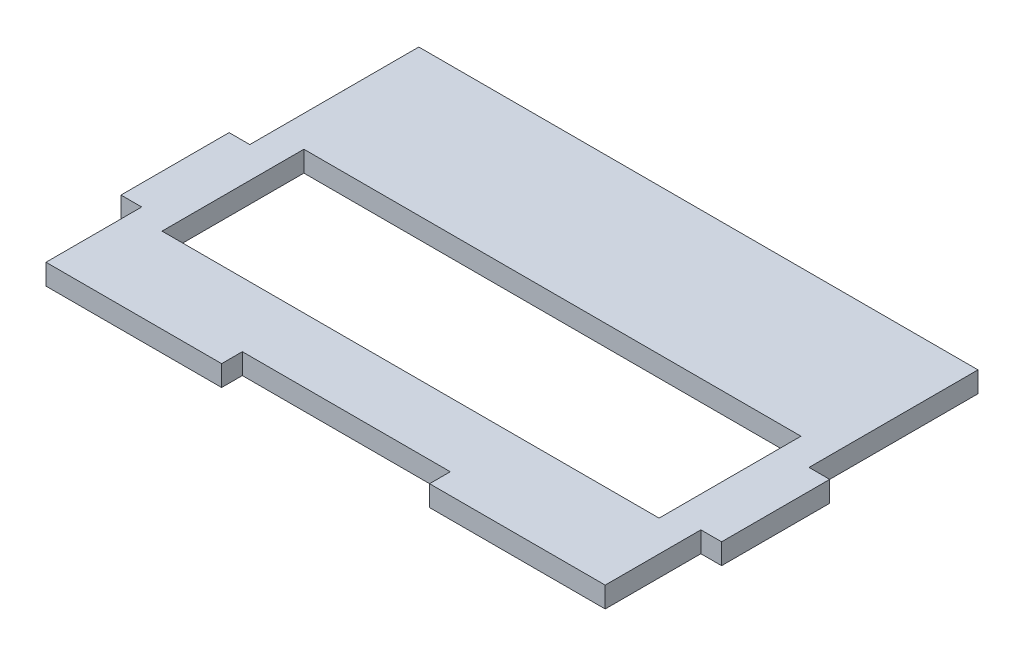
SolidWorks part; units mm, degrees
ref_plane "Front Plane" through (0, 0, 0) normal (0, 0, 1) x (1, 0, 0)
ref_plane "Top Plane" through (0, 0, 0) normal (0, 1, 0) x (1, 0, 0)
ref_plane "Right Plane" through (0, 0, 0) normal (1, 0, 0) x (0, 0, -1)
sketch "Sketch1" plane through (0, 0, 0) normal (0, 1, 0) x (1, 0, 0)
  line L1 (-72.5, -45) -> (72.5, -45)
  line L2 (-72.5, -45) -> (-72.5, 45)
  line L3 (-72.5, 45) -> (72.5, 45)
  line L4 (72.5, -45) -> (72.5, 45)
  line L5 (-72.5, -45) -> (72.5, 45) construction
  line L6 (-72.5, 45) -> (72.5, -45) construction
  point P0 (0, 0)
  dimension "D1" = 145
  dimension "D2" = 90
extrude "Boss-Extrude1" add sketch "Sketch1" along normal blind 5
sketch "Sketch3" plane through (0, 5, 0) normal (0, 1, 0) x (1, 0, 0)
  line L0 (0, -55) -> (0, 55) construction
  line L1 (-60, -24.49) -> (60, -24.49)
  line L2 (-60, -24.49) -> (-60, 9.76)
  line L3 (-60, 9.76) -> (60, 9.76)
  line L4 (60, -24.49) -> (60, 9.76)
  line L5 (-60, -24.49) -> (60, 9.76) construction
  line L6 (-60, 9.76) -> (60, -24.49) construction
  line L7 (-72.5, -45) -> (72.5, -45) construction
  point P0 (0, -7.365)
  dimension "D1" = 120
  dimension "D2" = 34.25
  dimension "D3" = 20.51
extrude "Cut-Extrude1" cut sketch "Sketch3" against normal blind 5
sketch "Sketch4" plane through (0, 5, 0) normal (0, 1, 0) x (1, 0, 0)
  line L0 (0, -2.75) -> (0, 2.75) construction
  line L1 (-72.5, 45) -> (-67.5, 45)
  line L2 (-72.5, 45) -> (-72.5, 4.2)
  line L3 (-72.5, 4.2) -> (-67.5, 4.2)
  line L4 (-67.5, 45) -> (-67.5, 4.2)
  line L5 (-72.5, -45) -> (-67.5, -45)
  line L6 (-72.5, -45) -> (-72.5, -21.9)
  line L7 (-72.5, -21.9) -> (-67.5, -21.9)
  line L8 (-67.5, -45) -> (-67.5, -21.9)
  line L9 (72.5, -21.9) -> (67.5, -21.9)
  line L10 (67.5, -45) -> (67.5, -21.9)
  line L11 (72.5, -45) -> (67.5, -45)
  line L12 (72.5, -45) -> (72.5, -21.9)
  line L13 (72.5, 4.2) -> (67.5, 4.2)
  line L14 (67.5, 45) -> (67.5, 4.2)
  line L15 (72.5, 45) -> (67.5, 45)
  line L16 (72.5, 45) -> (72.5, 4.2)
  dimension "D1" = 5
  dimension "D2" = 5
  dimension "D3" = 23.1
  dimension "D4" = 40.8
extrude "Cut-Extrude2" cut sketch "Sketch4" against normal blind 5
sketch "Sketch7" plane through (0, 5, 0) normal (0, 1, 0) x (1, 0, 0)
  line L0 (0, -2.75) -> (0, 2.75) construction
  line L1 (-25.1, -40) -> (25.1, -40)
  line L2 (-25.1, -40) -> (-25.1, -45)
  line L3 (-25.1, -45) -> (25.1, -45)
  line L4 (25.1, -40) -> (25.1, -45)
  line L5 (-25.1, -40) -> (25.1, -45) construction
  line L6 (-25.1, -45) -> (25.1, -40) construction
  line L7 (-67.5, -45) -> (67.5, -45) construction
  point P0 (0, -42.5)
  dimension "D1" = 5
  dimension "D2" = 50.2
extrude "Cut-Extrude3" cut sketch "Sketch7" against normal blind 5
